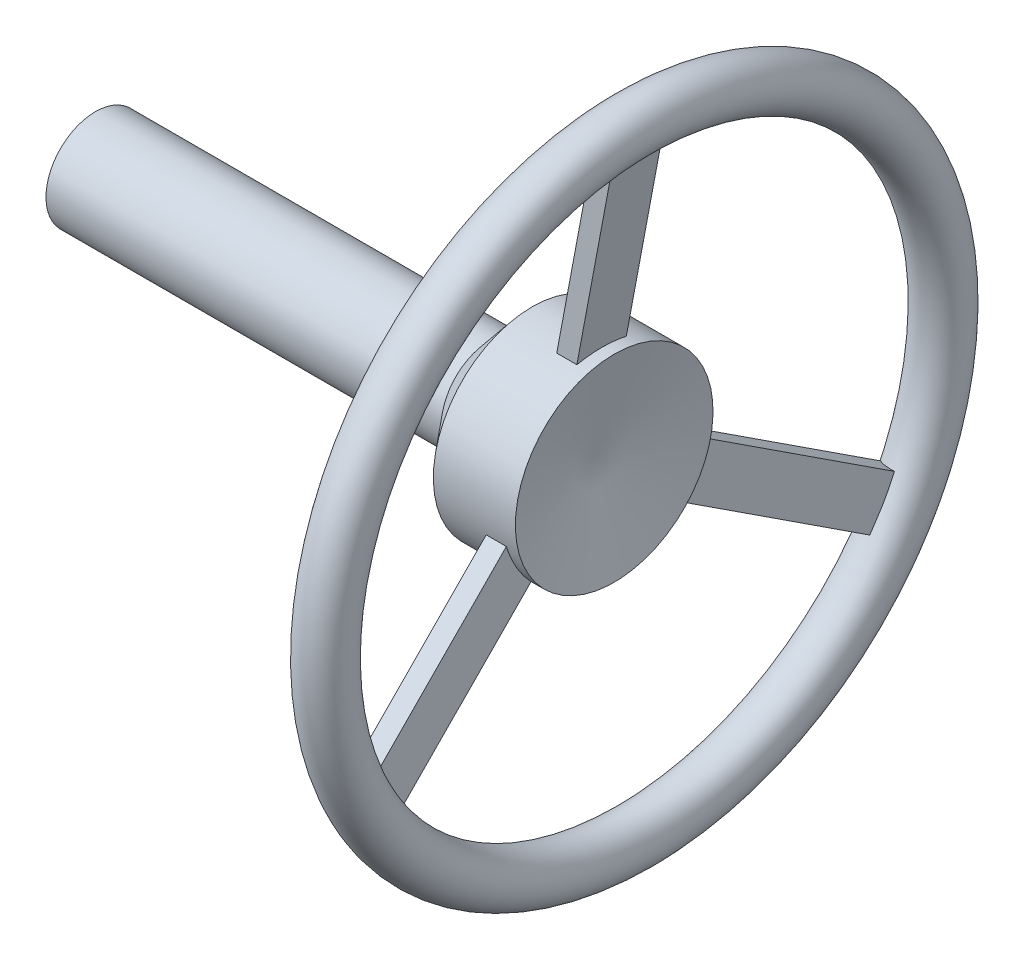
SolidWorks part; units mm, degrees
ref_plane "Ön Düzlem" through (0, 0, 0) normal (0, 0, 1) x (1, 0, 0)
ref_plane "Üst Düzlem" through (0, 0, 0) normal (0, 1, 0) x (1, 0, 0)
ref_plane "Sağ Düzlem" through (0, 0, 0) normal (1, 0, 0) x (0, 0, -1)
sketch "Çizim1" plane through (0, 0, 0) normal (0, 0, 1) x (1, 0, 0)
  line L0 (0.4724, 0) -> (0, 0) construction
  line L1 (0.4724, 0) -> (0.4724, 5)
  line L2 (0.4724, 5) -> (40.4724, 5)
  line L3 (40.4724, 5) -> (44.6679, 10)
  line L4 (44.6679, 10) -> (52.9679, 10)
  line L5 (52.9679, 10) -> (50.887, 0)
  line L6 (50.887, 0) -> (0.4724, 0)
  point P4 (7.8496, 0)
  point P9 (0, 0)
  point P10 (0, 0)
  point P11 (0, 0)
  point P12 (72.4115, 0)
  point P13 (56.308, 0)
  point P14 (5.9052, 0)
  point P15 (19.6807, 0)
  point P16 (0, 0)
  point P17 (5.285, 0)
  point P18 (52.4951, 0)
  point P19 (50.2735, 0)
  point P20 (0, 0)
  point P21 (0, 0)
  point P22 (0.4724, 0)
  dimension "D1" = 40
  dimension "D2" = 130
  dimension "D3" = 8.3
  dimension "D4" = 5
  dimension "D5" = 10
  dimension "D6" = 78.245
revolve "Döndür2" add sketch "Çizim1" angle 360 about L0
sketch "Çizim2" plane through (0, 0, 0) normal (0, 0, 1) x (1, 0, 0)
  line L0 (0, 0) -> (83.7799, 0) construction
  circle A0 centre (55, 31.25) radius 2.5
  dimension "D1" = 5
  dimension "D2" = 31.25
  dimension "D3" = 55
revolve "Döndür3" add sketch "Çizim2" angle 360 about L0
sketch "Çizim3" plane through (0, 0, 0) normal (0, 0, 1) x (1, 0, 0)
  line L0 (51.6, 9.2) -> (49.5649, 9.2)
  line L1 (49.5649, 9.2) -> (53.9849, 32.6938)
  line L2 (53.9849, 32.6938) -> (56.02, 32.6938)
  line L3 (56.02, 32.6938) -> (51.6, 9.2)
  line L4 (52.5, 31.25) -> (52.5, -31.25) construction
  point P7 (0, 0)
  dimension "D1" = 2
  dimension "D2" = 9.2
  dimension "D3" = 0.9
  dimension "D4" = 4.42
  dimension "D5" = 56.02
extrude "Yükseklik-Ekstrüzyon1" add sketch "Çizim3" along normal mid plane 5
pattern_circular "Dairesel Kaplama1" count 3 over 360 about axis through (0, 0, 0) along (1, 0, 0) of "Yükseklik-Ekstrüzyon1"
